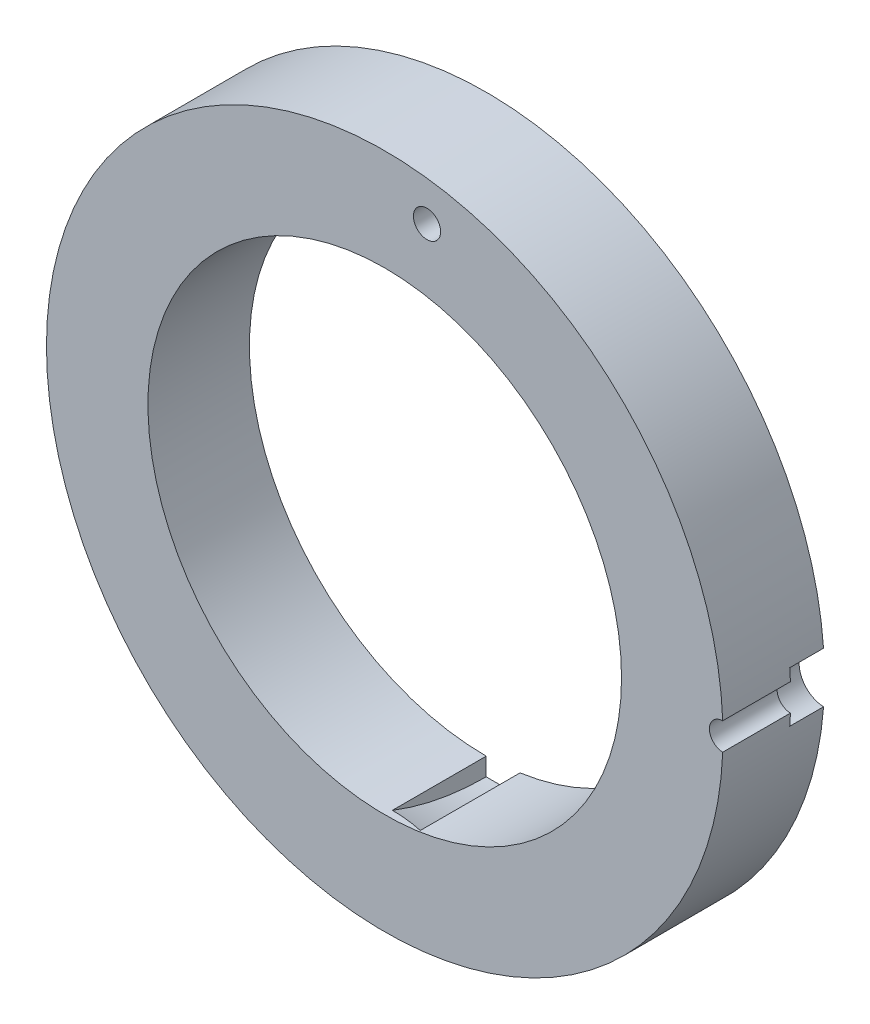
SolidWorks part; units mm, degrees
ref_plane "Front Plane" through (0, 0, 0) normal (0, 0, 1) x (1, 0, 0)
ref_plane "Top Plane" through (0, 0, 0) normal (0, 1, 0) x (1, 0, 0)
ref_plane "Right Plane" through (0, 0, 0) normal (1, 0, 0) x (0, 0, -1)
sketch "Sketch1" plane through (0, 0, 0) normal (0, 0, 1) x (1, 0, 0)
  circle A0 centre (0, 0) radius 63.5
extrude "Boss-Extrude1" add sketch "Sketch1" along normal blind 19.05
sketch "Sketch2" plane through (0, 0, 0) normal (0, 0, 1) x (1, 0, 0)
  circle A0 centre (0, 0) radius 44.45
extrude "Cut-Extrude1" cut sketch "Sketch2" along normal through all
sketch "Sketch3" plane through (0, 0, 0) normal (1, 0, 0) x (0, 0, -1)
  circle A0 centre (0, 0) radius 47.8155
extrude "Cut-Extrude2" cut sketch "Sketch3" along normal blind 6.35
sketch "Sketch4" plane through (0, 0, 0) normal (0, 0, 1) x (1, 0, 0)
  circle A0 centre (63.5, 111.125) radius 2.5527
  circle A1 centre (7.9375, 55.5625) radius 2.5527
  circle A2 centre (63.5, 0) radius 2.5527
  circle A3 centre (0, 0) radius 63.5 construction
  circle A4 centre (119.0625, 55.5625) radius 2.5527
extrude "Cut-Extrude3" cut sketch "Sketch4" along normal through all
sketch "Sketch5" plane through (0, 0, 0) normal (0, 0, 1) x (1, 0, 0)
  circle A0 centre (63.5, 111.125) radius 4.7625
  circle A1 centre (7.9375, 55.5625) radius 4.7625
  circle A2 centre (63.5, 0) radius 4.7625
  circle A3 centre (119.0625, 55.5625) radius 4.7625
extrude "Cut-Extrude4" cut sketch "Sketch5" along normal blind 6.35
